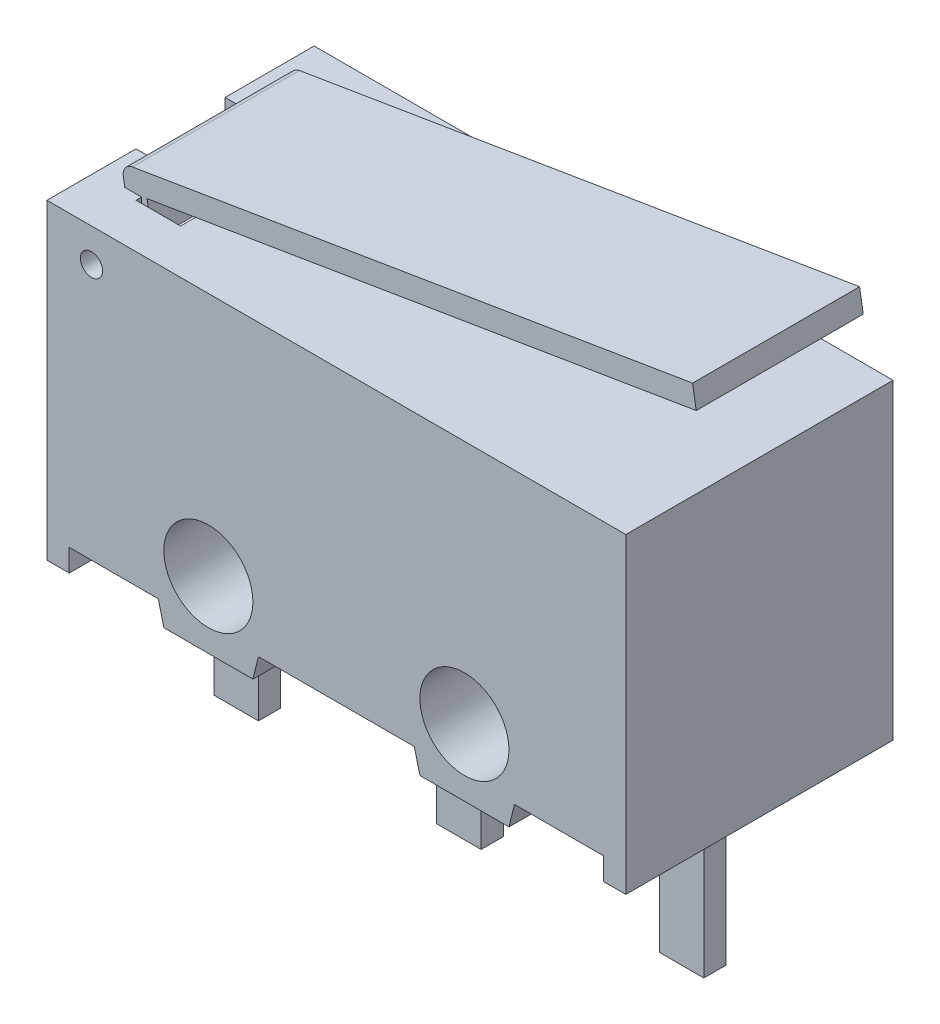
SolidWorks part; units mm, degrees
ref_plane "Front Plane" through (0, 0, 0) normal (0, 0, 1) x (1, 0, 0)
ref_plane "Top Plane" through (0, 0, 0) normal (0, 1, 0) x (1, 0, 0)
ref_plane "Right Plane" through (0, 0, 0) normal (1, 0, 0) x (0, 0, -1)
sketch "Sketch1" plane through (0, 0, 0) normal (0, 0, 1) x (1, 0, 0)
  line L0 (-6, -3.5) -> (-6, -3)
  line L1 (-6.5, 3.5) -> (6.5, 3.5)
  line L2 (-6.5, 3.5) -> (-6.5, -3.5)
  line L3 (-6.5, -3.5) -> (6.5, -3.5)
  line L4 (6.5, 3.5) -> (6.5, -3.5)
  line L5 (-6.5, 3.5) -> (6.5, -3.5) construction
  line L6 (-6.5, -3.5) -> (6.5, 3.5) construction
  line L7 (-6, -3) -> (-4, -3)
  line L8 (-4, -3) -> (-3.875, -3.5)
  line L9 (-1.875, -3.5) -> (-1.75, -3)
  line L10 (-1.75, -3) -> (1.75, -3)
  line L11 (1.75, -3) -> (1.875, -3.5)
  line L12 (6, -3.5) -> (6, -3)
  line L13 (6, -3) -> (4, -3)
  line L14 (4, -3) -> (3.875, -3.5)
  point P4 (0, 0)
  point P16 (-1.2335, -3.5)
  point P19 (0.5876, -3)
  point P20 (-1.5, -3)
  point P21 (0, 0)
  dimension "D1" = 7
  dimension "D2" = 13
  dimension "D3" = 0.5
  dimension "D4" = 0.5
  dimension "D5" = 0.5
  dimension "D6" = 2
  dimension "D7" = 2
  dimension "D8" = 3.5
  dimension "D9" = 2
extrude "Boss-Extrude1" add sketch "Sketch1" along normal mid plane 6 contours L14 L13 L12 L3 L4 L1 L2 L0 L7 L8 L9 L10 L11
sketch "Sketch2" plane through (0, 0, 0) normal (0, 0, 1) x (1, 0, 0)
  line L0 (-3.875, -3.5) -> (-1.875, -3.5) construction
  line L1 (1.875, -3.5) -> (3.875, -3.5) construction
  circle A0 centre (-2.875, -2) radius 1
  circle A1 centre (2.875, -2) radius 1
  point P4 (0, 0)
  point P5 (-2.875, -3.5)
  point P6 (2.875, -3.5)
  dimension "D1" = 1.5
  dimension "D2" = 2
extrude "Cut-Extrude1" cut sketch "Sketch2" against normal through all both and the other way through all
sketch "Sketch3" plane through (0, -3, 0) normal (0, -1, 0) x (1, 0, 0)
  line L13 (-0.5, 0.25) -> (0.5, 0.25)
  line L14 (-0.5, 0.25) -> (-0.5, -0.25)
  line L15 (-0.5, -0.25) -> (0.5, -0.25)
  line L16 (0.5, 0.25) -> (0.5, -0.25)
  line L17 (-0.5, 0.25) -> (0.5, -0.25) construction
  line L18 (-0.5, -0.25) -> (0.5, 0.25) construction
  line L19 (-5.5, 0.25) -> (-4.5, 0.25)
  line L20 (-5.5, 0.25) -> (-5.5, -0.25)
  line L21 (-5.5, -0.25) -> (-4.5, -0.25)
  line L22 (-4.5, 0.25) -> (-4.5, -0.25)
  line L23 (-5.5, 0.25) -> (-4.5, -0.25) construction
  line L24 (-5.5, -0.25) -> (-4.5, 0.25) construction
  line L25 (4.5, 0.25) -> (5.5, 0.25)
  line L26 (4.5, 0.25) -> (4.5, -0.25)
  line L27 (4.5, -0.25) -> (5.5, -0.25)
  line L28 (5.5, 0.25) -> (5.5, -0.25)
  line L29 (4.5, 0.25) -> (5.5, -0.25) construction
  line L30 (4.5, -0.25) -> (5.5, 0.25) construction
  point P4 (0, 0)
  point P9 (-5, 0)
  point P14 (5, 0)
  point P15 (0, 0)
  point P16 (0, 0)
  point P18 (0, 0)
  point P19 (0, 0)
  point P20 (-5.2431, 0)
  dimension "D1" = 1
  dimension "D2" = 0.5
  dimension "D3" = 5
  dimension "D4" = 5
extrude "Boss-Extrude2" add sketch "Sketch3" along normal blind 4 separate body
sketch "Sketch5" plane through (0, 0, 0) normal (0, 0, 1) x (1, 0, 0)
  line L0 (-6.5, 3.5) -> (-6.5, -3.5) construction
  line L1 (-6.5, 3.5) -> (6.5, 3.5) construction
  circle A0 centre (-5.5, 2.75) radius 0.25
  dimension "D1" = 1
  dimension "D3" = 0.5
  dimension "D2" = 0.75
extrude "Cut-Extrude2" cut sketch "Sketch5" against normal through all both and the other way through all
sketch "Sketch6" plane through (0, 3.5, 0) normal (0, 1, 0) x (1, 0, 0)
  line L0 (-6.5, -3) -> (-6.5, 3) construction
  line L1 (-4.5, 2) -> (-5.5, 2)
  line L2 (-4.5, 2) -> (-4.5, -2)
  line L3 (-4.5, -2) -> (-5.5, -2)
  line L4 (-5.5, 2) -> (-5.5, -2)
  line L5 (-4.5, 2) -> (-5.5, -2) construction
  line L6 (-4.5, -2) -> (-5.5, 2) construction
  line L7 (-5.5, 1) -> (-6.5, 1)
  line L8 (-5.5, 1) -> (-5.5, -1)
  line L9 (-5.5, -1) -> (-6.5, -1)
  line L10 (-6.5, 1) -> (-6.5, -1)
  line L11 (-5.5, 1) -> (-6.5, -1) construction
  line L12 (-5.5, -1) -> (-6.5, 1) construction
  point P4 (-5, 0)
  point P9 (-6, 0)
  point P12 (0, 0)
  point P13 (0, 0)
  point P15 (0, 0)
  line M6 (-6.5, 3) -> (-6.5, -3)
  dimension "D1" = 4
  dimension "D2" = 2
  dimension "D3" = 1
  dimension "D4" = 1
extrude "Cut-Extrude3" cut sketch "Sketch6" against normal blind 2 contours L1 L4 L3 L2 | L9 L4 L7 M6
sketch "Sketch4" plane through (0, 0, 0) normal (0, 0, 1) x (1, 0, 0)
  line L0 (-5.7045, 3.9832) -> (6.8738, 6.0688)
  line L1 (6.8738, 6.0688) -> (6.9556, 5.5755)
  line L2 (6.9556, 5.5755) -> (-5.8693, 3.449)
  line L3 (-5.8693, 3.449) -> (-5.9102, 3.6956)
  line L4 (-5.8693, 3.449) -> (-5.7466, 2.7091)
  line L5 (-5.7466, 2.7091) -> (-5.2534, 2.7909)
  line L6 (-5.2534, 2.7909) -> (-5.3761, 3.5308)
  line L7 (6.5, 3.5) -> (6.5, 5.5) construction
  arc A0 (-5.7045, 3.9832) -> (-5.9102, 3.6956) centre (-5.6636, 3.7365) ccw
  point P7 (-5.5, 2.75)
  point P11 (-5.9511, 3.9423)
  point P15 (0, 0)
  dimension "D5" = 0.25
  dimension "D1" = 0.5
  dimension "D2" = 13
  dimension "D3" = 1.25
  dimension "D4" = 2
extrude "Boss-Extrude3" add sketch "Sketch4" along normal mid plane 3.75 separate body contours L3 L2 L1 L0 | L5 L6 L2 L4
equation "\"D5@Sketch1\"=\"D4@Sketch1\""
equation "\"D4@Sketch3\"=\"D3@Sketch3\""
